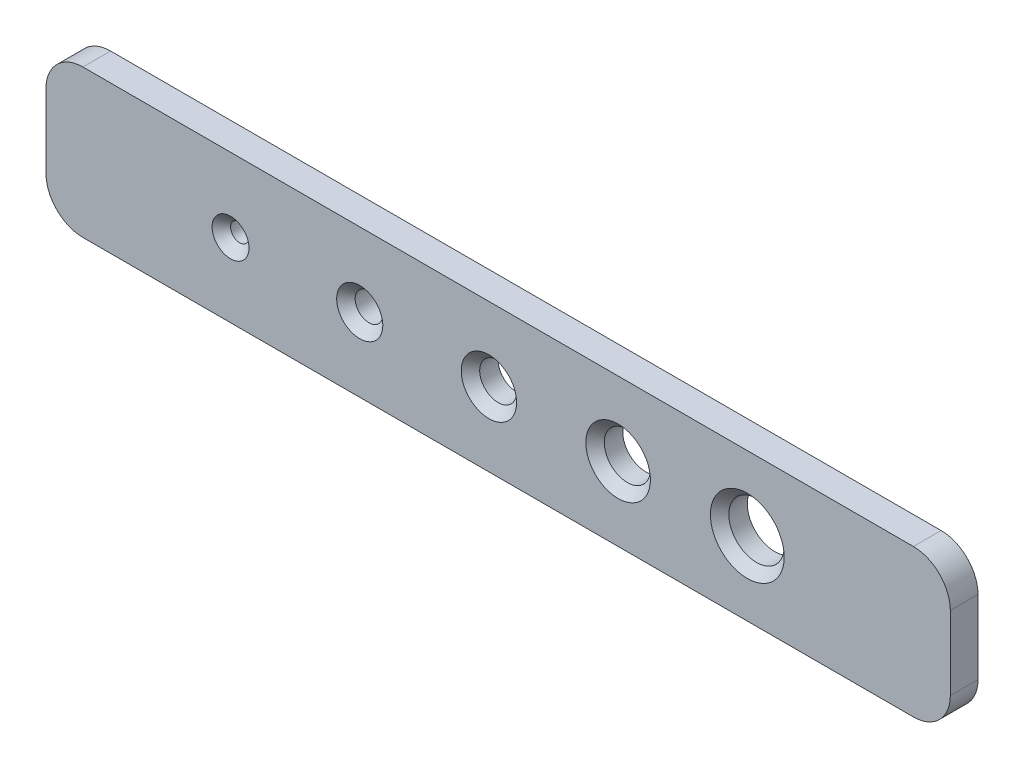
SolidWorks part; units mm, degrees
ref_plane "Front Plane" through (0, 0, 0) normal (0, 0, 1) x (1, 0, 0)
ref_plane "Top Plane" through (0, 0, 0) normal (0, 1, 0) x (1, 0, 0)
ref_plane "Right Plane" through (0, 0, 0) normal (1, 0, 0) x (0, 0, -1)
sketch "Sketch2" plane through (0, 0, 0) normal (0, 0, 1) x (1, 0, 0)
  line L1 (0, 0) -> (155.575, 0)
  line L2 (0, 0) -> (0, 25.4)
  line L3 (0, 25.4) -> (155.575, 25.4)
  line L4 (155.575, 0) -> (155.575, 25.4)
  dimension "D1" = 155.575
  dimension "D2" = 25.4
extrude "Boss-Extrude2" add sketch "Sketch2" along normal blind 4.7625
sketch "Sketch3" plane through (0, 0, 4.7625) normal (0, 0, 1) x (1, 0, 0)
  line L0 (31.75, 22.225) -> (31.75, 3.175) construction
  line L1 (0, 25.4) -> (0, 0) construction
  line L2 (53.975, 22.225) -> (53.975, 3.175) construction
  line L3 (76.2, 22.225) -> (76.2, 3.175) construction
  line L4 (98.425, 22.225) -> (98.425, 3.175) construction
  line L5 (120.65, 22.225) -> (120.65, 3.175) construction
  line L6 (0, 0) -> (155.575, 0) construction
  line L7 (141.2875, 12.7) -> (14.2875, 12.7) construction
  line L8 (155.575, 0) -> (155.575, 25.4) construction
  circle A0 centre (31.75, 12.7) radius 1.5875
  circle A1 centre (53.975, 12.7) radius 2.3812
  circle A2 centre (76.2, 12.7) radius 3.175
  circle A3 centre (98.425, 12.7) radius 3.9688
  circle A4 centre (120.65, 12.7) radius 4.7625
  dimension "D14" = 3.175
  dimension "D15" = 4.7625
  dimension "D16" = 6.35
  dimension "D17" = 7.9375
  dimension "D18" = 9.525
  dimension "D1" = 31.75
  dimension "D2" = 53.975
  dimension "D3" = 76.2
  dimension "D4" = 98.425
  dimension "D5" = 120.65
  dimension "D6" = 19.05
  dimension "D7" = 3.175
  dimension "D8" = 3.175
  dimension "D9" = 3.175
  dimension "D10" = 3.175
  dimension "D11" = 3.175
  dimension "D12" = 14.2875
  dimension "D13" = 127
fillet "Fillet1" radius 6.35 4 edges at (0, 25.4, 2.3813) (0, 0, 2.3813) (155.575, 0, 2.3813) (155.575, 25.4, 2.3813)
extrude "Cut-Extrude1" cut sketch "Sketch3" against normal through all contours A4 | A3 | A2 | A1 | A0
hole_wizard "CSK for M10 Flat Head Machine Screw3" positions "3DSketch7" profile "Sketch11" countersink size "M10" standard "ANSI Metric" end condition through all
sketch3d "3DSketch7"
  line L0 (31.75, 12.7, 0) -> (31.75, 12.7, 4.7625) construction
  point P0 (31.75, 12.7, 4.7625)
sketch "Sketch11" plane through (31.75, 12.7, 4.7625) normal (1, 0, 0) x (0, -1, 0)
  line L0 (0, 0) -> (0, 4.7625)
  line L1 (0, 4.7625) -> (1.5875, 4.7625)
  line L2 (1.5875, 4.7625) -> (1.5875, 1.5875)
  line L3 (1.5875, 1.5875) -> (3.175, 0)
  line L5 (3.175, 0) -> (0, 0)
  line L6 (-1.5875, 1.5875) -> (-3.175, 0) construction
  line L11 (0, -6.35) -> (0, 107.95) construction
  dimension "Thru Hole Dia." = 3.175
  dimension "Thru Hole Depth" = 4.7625
  dimension "Near C'Sink Dia." = 6.35
  dimension "Near C'Sink Angle" = 90
hole_wizard "CSK for M10 Flat Head Machine Screw4" positions "3DSketch8" profile "Sketch12" countersink size "M10" standard "ANSI Metric" end condition through all
sketch3d "3DSketch8"
  line L0 (53.975, 12.7, 0) -> (53.975, 12.7, 4.7625) construction
  point P0 (53.975, 12.7, 4.7625)
sketch "Sketch12" plane through (53.975, 12.7, 4.7625) normal (1, 0, 0) x (0, -1, 0)
  line L0 (0, 0) -> (0, 4.7625)
  line L1 (0, 4.7625) -> (2.3812, 4.7625)
  line L2 (2.3812, 4.7625) -> (2.3812, 1.5875)
  line L3 (2.3812, 1.5875) -> (3.9688, 0)
  line L5 (3.9688, 0) -> (0, 0)
  line L6 (-2.3812, 1.5875) -> (-3.9688, 0) construction
  line L11 (0, -6.35) -> (0, 107.95) construction
  dimension "Thru Hole Dia." = 4.7625
  dimension "Thru Hole Depth" = 4.7625
  dimension "Near C'Sink Dia." = 7.9375
  dimension "Near C'Sink Angle" = 90
hole_wizard "CSK for M10 Flat Head Machine Screw5" positions "3DSketch9" profile "Sketch13" countersink size "M10" standard "ANSI Metric" end condition through all
sketch3d "3DSketch9"
  line L0 (76.2, 12.7, 0) -> (76.2, 12.7, 4.7625) construction
  point P0 (76.2, 12.7, 4.7625)
sketch "Sketch13" plane through (76.2, 12.7, 4.7625) normal (1, 0, 0) x (0, -1, 0)
  line L0 (0, 0) -> (0, 4.7625)
  line L1 (0, 4.7625) -> (3.175, 4.7625)
  line L2 (3.175, 4.7625) -> (3.175, 1.5875)
  line L3 (3.175, 1.5875) -> (4.7625, 0)
  line L5 (4.7625, 0) -> (0, 0)
  line L6 (-3.175, 1.5875) -> (-4.7625, 0) construction
  line L11 (0, -6.35) -> (0, 107.95) construction
  dimension "Thru Hole Dia." = 6.35
  dimension "Thru Hole Depth" = 4.7625
  dimension "Near C'Sink Dia." = 9.525
  dimension "Near C'Sink Angle" = 90
hole_wizard "CSK for M10 Flat Head Machine Screw6" positions "3DSketch10" profile "Sketch14" countersink size "M10" standard "ANSI Metric" end condition through all
sketch3d "3DSketch10"
  line L0 (98.425, 12.7, 0) -> (98.425, 12.7, 4.7625) construction
  point P0 (98.425, 12.7, 4.7625)
sketch "Sketch14" plane through (98.425, 12.7, 4.7625) normal (1, 0, 0) x (0, -1, 0)
  line L0 (0, 0) -> (0, 4.7625)
  line L1 (0, 4.7625) -> (3.9687, 4.7625)
  line L2 (3.9687, 4.7625) -> (3.9688, 1.5875)
  line L3 (3.9688, 1.5875) -> (5.5563, 0)
  line L5 (5.5563, 0) -> (0, 0)
  line L6 (-3.9688, 1.5875) -> (-5.5563, 0) construction
  line L11 (0, -6.35) -> (0, 107.95) construction
  dimension "Thru Hole Dia." = 7.9375
  dimension "Thru Hole Depth" = 4.7625
  dimension "Near C'Sink Dia." = 11.1125
  dimension "Near C'Sink Angle" = 90
hole_wizard "CSK for M10 Flat Head Machine Screw7" positions "3DSketch11" profile "Sketch15" countersink size "M10" standard "ANSI Metric" end condition through all
sketch3d "3DSketch11"
  line L0 (120.65, 12.7, 0) -> (120.65, 12.7, 4.7625) construction
  point P0 (120.65, 12.7, 4.7625)
sketch "Sketch15" plane through (120.65, 12.7, 4.7625) normal (1, 0, 0) x (0, -1, 0)
  line L0 (0, 0) -> (0, 4.7625)
  line L1 (0, 4.7625) -> (4.7625, 4.7625)
  line L2 (4.7625, 4.7625) -> (4.7625, 1.5875)
  line L3 (4.7625, 1.5875) -> (6.35, 0)
  line L5 (6.35, 0) -> (0, 0)
  line L6 (-4.7625, 1.5875) -> (-6.35, 0) construction
  line L11 (0, -6.35) -> (0, 107.95) construction
  dimension "Thru Hole Dia." = 9.525
  dimension "Thru Hole Depth" = 4.7625
  dimension "Near C'Sink Dia." = 12.7
  dimension "Near C'Sink Angle" = 90
